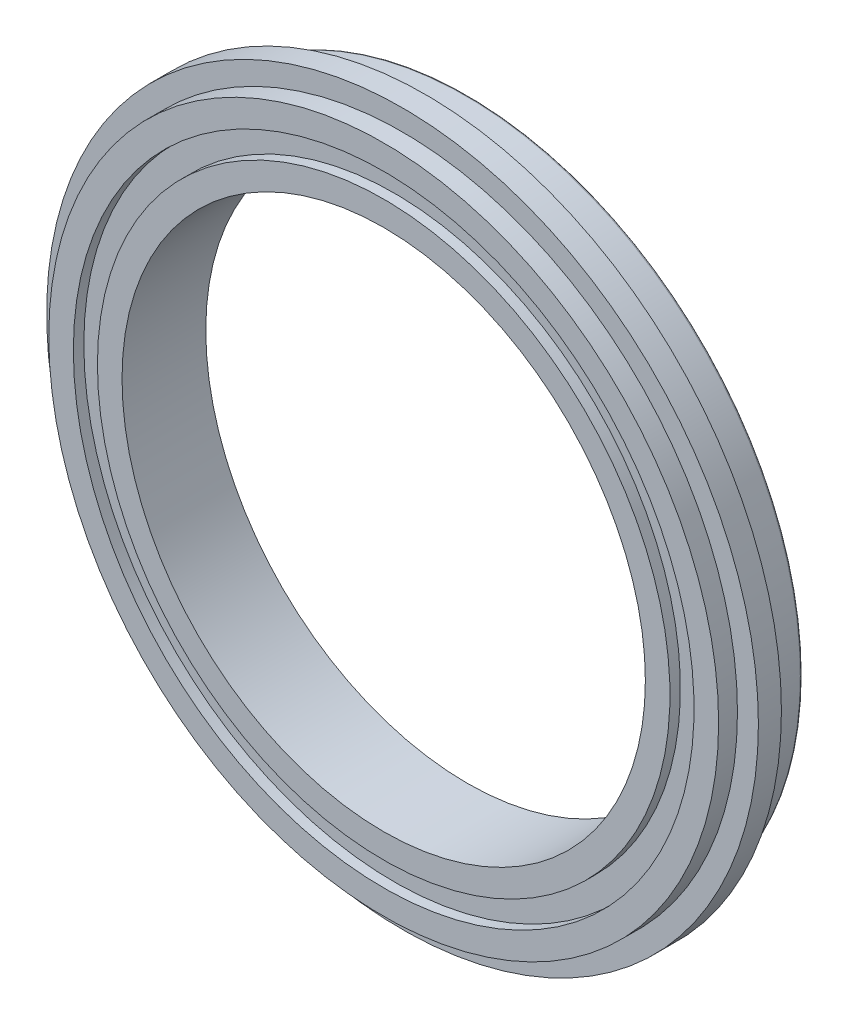
SolidWorks part; units mm, degrees
material "1.5714 (16NiCr4)"
ref_plane "前视基准面" through (0, 0, 0) normal (0, 0, 1) x (1, 0, 0)
ref_plane "上视基准面" through (0, 0, 0) normal (0, 1, 0) x (1, 0, 0)
ref_plane "右视基准面" through (0, 0, 0) normal (1, 0, 0) x (0, 0, -1)
sketch "草图1" plane through (0, 0, 0) normal (0, 0, 1) x (1, 0, 0)
  circle A0 centre (0, 0) radius 12.5
  circle A1 centre (0, 0) radius 16
  dimension "D1" = 25
  dimension "D2" = 32
extrude "凸台-拉伸1" add sketch "草图1" along normal blind 4
sketch "草图2" plane through (0, 0, 4) normal (0, 0, 1) x (1, 0, 0)
  circle A0 centre (0, 0) radius 17
  circle A1 centre (0, 0) radius 16
  dimension "D1" = 32
  dimension "D2" = 34
extrude "凸台-拉伸2" add sketch "草图2" against normal blind 1.1 from offset 0.9 offset against normal yes
fillet "圆角1" radius 0.1 1 edges at (16, 0, 0)
sketch "草图3" plane through (0, 0, 0) normal (1, 0, 0) x (0, 0, -1)
  line L0 (0, 0) -> (0, 16.148) construction
  line L1 (0, 0) -> (-6.5785, 0) construction
  line L3 (-3.1, 17) -> (-3.1, -17) construction
  line L4 (-3.1, 17) -> (-3.1, -17) construction
  line L5 (-0.5, 13.675) -> (0, 13.675)
  line L6 (-0.5, 13.675) -> (-0.5, 14.825)
  line L7 (-0.5, 14.825) -> (0, 14.825)
  line L8 (0, 13.675) -> (0, 14.825)
  line L9 (-0.5, 13.675) -> (0, 14.825) construction
  line L10 (-0.5, 14.825) -> (0, 13.675) construction
  line L16 (-2.6, 13.675) -> (-3.1, 13.675)
  line L17 (-2.6, 13.675) -> (-2.6, 14.825)
  line L18 (-2.6, 14.825) -> (-3.1, 14.825)
  line L19 (-3.1, 13.675) -> (-3.1, 14.825)
  line L20 (-2.6, 13.675) -> (-3.1, 14.825) construction
  line L21 (-2.6, 14.825) -> (-3.1, 13.675) construction
  point P6 (-0.25, 14.25)
  point P11 (-2.85, 14.25)
  dimension "D1" = 0.5
  dimension "D2" = 27.35
  dimension "D3" = 29.65
revolve "切除-旋转1" cut sketch "草图3" angle 360 about L1
ref_plane "基准面1" through (0, 0, 2) normal (0, 0, -1) x (-1, 0, 0)
mirror "镜向1" about plane through (0, 0, 2) normal (0, 0, -1) of "切除-旋转1"
move or copy body "实体-移动/复制1" [suppressed] bodies to move or copy 102
